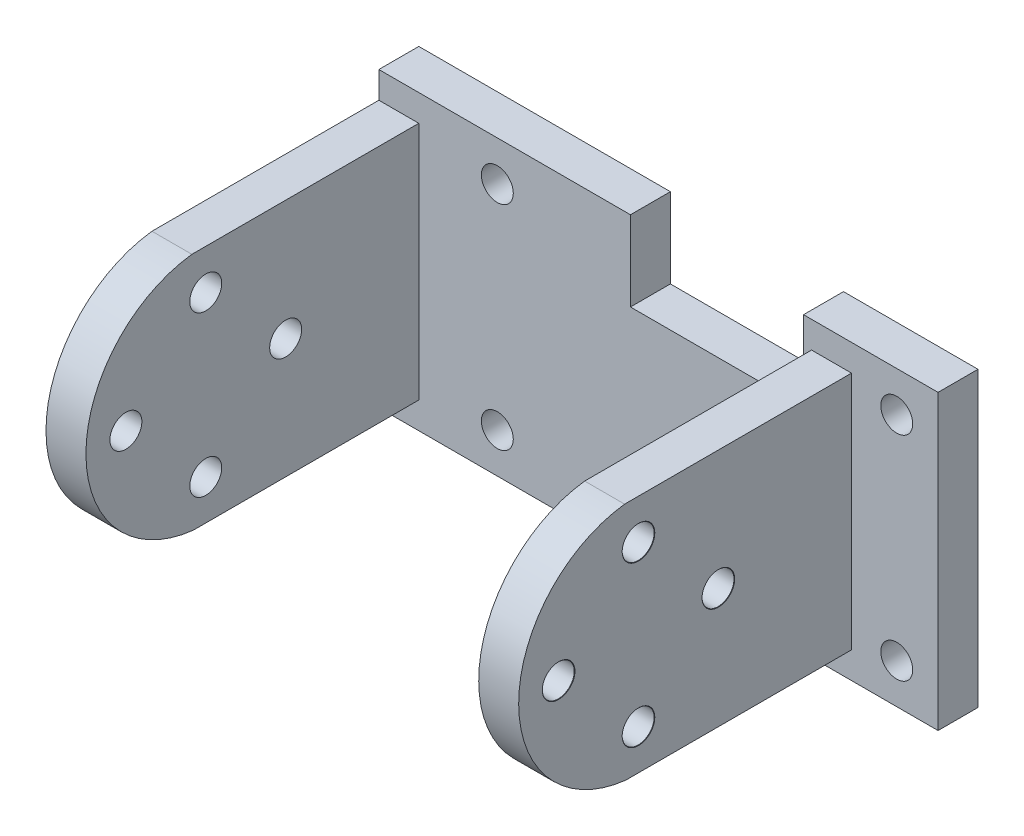
SolidWorks part; units mm, degrees
ref_plane "Front Plane" through (0, 0, 0) normal (0, 0, 1) x (1, 0, 0)
ref_plane "Top Plane" through (0, 0, 0) normal (0, 1, 0) x (1, 0, 0)
ref_plane "Right Plane" through (0, 0, 0) normal (1, 0, 0) x (0, 0, -1)
ref_plane "Plane1" through (0, 0, 47.8926) normal (0, 0, 1) x (1, 0, 0)
sketch "Sketch1" plane through (0, 0, 47.8926) normal (0, 0, 1) x (1, 0, 0)
  line L0 (29.75, 233.2226) -> (-12.25, 233.2226)
  line L1 (-12.25, 233.2226) -> (-12.25, 211.2226)
  line L2 (-12.25, 211.2226) -> (29.75, 211.2226)
  line L3 (29.75, 211.2226) -> (29.75, 233.2226)
extrude "Boss-Extrude1" add sketch "Sketch1" against normal blind 3
sketch "Sketch2" plane through (0, 0, 44.8926) normal (0, 0, -1) x (-1, 0, 0)
  line L0 (-6.6467, 233.2226) -> (-19.6467, 233.2226)
  line L1 (-19.6467, 233.2226) -> (-19.6467, 227.2226)
  line L2 (-19.6467, 227.2226) -> (-6.6467, 227.2226)
  line L3 (-6.6467, 227.2226) -> (-6.6467, 233.2226)
extrude "Cut-Extrude1" cut sketch "Sketch2" against normal through all
sketch "Sketch3" plane through (0, 0, 44.8926) normal (0, 0, -1) x (-1, 0, 0)
  line L0 (-19.6467, 211.2226) -> (-6.6467, 211.2226)
  line L1 (-6.6467, 211.2226) -> (-6.6467, 217.2226)
  line L2 (-6.6467, 217.2226) -> (-19.6467, 217.2226)
  line L3 (-19.6467, 217.2226) -> (-19.6467, 211.2226)
extrude "Cut-Extrude2" cut sketch "Sketch3" against normal through all
ref_plane "Plane2" through (-12.25, 0, 0) normal (-1, 0, 0) x (0, -1, 0)
sketch "Sketch4" plane through (-12.25, 0, 0) normal (-1, 0, 0) x (0, -1, 0)
  line L0 (-231.2226, 64.9357) -> (-231.2226, 47.8926)
  line L1 (-231.2226, 47.8926) -> (-213.2226, 47.8926)
  line L2 (-213.2226, 47.8926) -> (-213.2226, 64.8395)
  arc A0 (-213.2226, 64.8395) -> (-231.2226, 64.9357) centre (-222.2283, 63.8306) ccw
extrude "Boss-Extrude2" add sketch "Sketch4" against normal blind 3
ref_plane "Plane3" through (23.25, 0, 0) normal (1, 0, 0) x (0, 0, -1)
sketch "Sketch5" plane through (23.25, 0, 0) normal (1, 0, 0) x (0, 0, -1)
  line L0 (-64.8395, 213.2226) -> (-47.8926, 213.2226)
  line L1 (-47.8926, 213.2226) -> (-47.8926, 231.2226)
  line L2 (-47.8926, 231.2226) -> (-64.9357, 231.2226)
  arc A0 (-64.9357, 231.2226) -> (-64.8395, 213.2226) centre (-63.8306, 222.2283) ccw
extrude "Boss-Extrude3" add sketch "Sketch5" against normal blind 3
hole_wizard "M2 Clearance Hole1" positions "Sketch7" profile "Sketch6" hole size "M2" standard "ANSI Metric" end condition through all
sketch "Sketch7" plane through (23.25, 0, 0) normal (1, 0, 0) x (0, 0, -1)
  point P0 (-63.8928, 228.2222)
  point P1 (-69.8926, 222.2224)
  point P2 (-63.8928, 216.2226)
  point P3 (-57.893, 222.2224)
sketch "Sketch6" plane through (23.25, 228.2222, 63.8928) normal (0, 1, 0) x (0, 0, -1)
  line L0 (0, 0) -> (0, 35.5)
  line L1 (0, 35.5) -> (1.2, 35.5)
  line L2 (1.2, 35.5) -> (1.2, 0.025)
  line L3 (1.2, 0.025) -> (1.225, 0)
  line L5 (1.225, 0) -> (0, 0)
  line L6 (-1.2, 0.025) -> (-1.225, 0) construction
  line L11 (0, -6.35) -> (0, 107.95) construction
  dimension "Thru Hole Dia." = 2.4
  dimension "Thru Hole Depth" = 35.5
  dimension "Near C'Sink Dia." = 2.45
  dimension "Near C'Sink Angle" = 90
hole_wizard "M2 Clearance Hole2" positions "Sketch9" profile "Sketch8" hole size "M2" standard "ANSI Metric" end condition through all
sketch "Sketch9" plane through (0, 0, 47.8926) normal (0, 0, 1) x (1, 0, 0)
  point P0 (-3.3533, 230.215)
  point P1 (-3.3533, 214.215)
  point P2 (26.6467, 214.215)
  point P3 (26.6467, 230.215)
sketch "Sketch8" plane through (-3.3533, 230.215, 47.8926) normal (1, 0, 0) x (0, -1, 0)
  line L0 (0, 0) -> (0, 3)
  line L1 (0, 3) -> (1.2, 3)
  line L2 (1.2, 3) -> (1.2, 0)
  line L5 (1.2, 0) -> (0, 0)
  line L11 (0, -6.35) -> (0, 107.95) construction
  dimension "Thru Hole Dia." = 2.4
  dimension "Thru Hole Depth" = 3
ref_plane "Plane4" through (5.5, 0, 0) normal (1, 0, 0) x (0, 0, -1)
